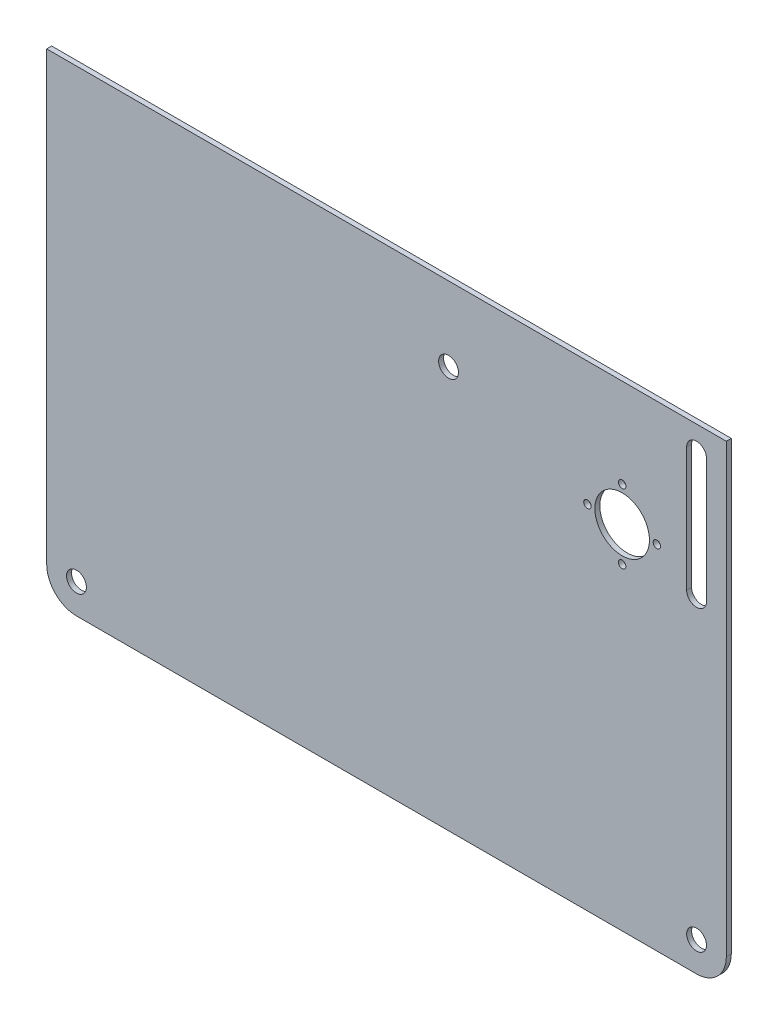
SolidWorks part; units mm, degrees
ref_plane "Front Plane" through (0, 0, 0) normal (0, 0, 1) x (1, 0, 0)
ref_plane "Top Plane" through (0, 0, 0) normal (0, 1, 0) x (1, 0, 0)
ref_plane "Right Plane" through (0, 0, 0) normal (1, 0, 0) x (0, 0, -1)
sketch "Sketch1" plane through (0, 0, 0) normal (0, 0, 1) x (1, 0, 0)
  line L0 (55, 0) -> (-55, 0) construction
  line L1 (0, 53.2731) -> (0, -38.9774) construction
  line L2 (0, -55) -> (0, 55) construction
  line L3 (-125, -12) -> (125, -12)
  line L4 (121, 120) -> (129, 120)
  line L5 (121, 120) -> (121, 170)
  line L6 (121, 170) -> (129, 170)
  line L7 (129, 120) -> (129, 170)
  line L8 (121, 120) -> (129, 170) construction
  line L9 (121, 170) -> (129, 120) construction
  line L10 (158.4448, 180) -> (-53.9982, 180)
  line L11 (137, 0) -> (137, 180)
  line L12 (137, 180) -> (158.4448, 180)
  line L13 (-53.9982, 180) -> (-137, 180)
  line L14 (-137, 180) -> (-137, 0)
  circle A0 centre (-125, 0) radius 4
  circle A1 centre (125, 0) radius 4
  circle A2 centre (125, 170) radius 4
  circle A3 centre (95, 130) radius 11
  circle A4 centre (25, 150) radius 4
  circle A5 centre (125, 120) radius 4
  arc A6 (-125, -12) -> (-137, 0) centre (-125, 0) cw
  arc A7 (125, -12) -> (137, 0) centre (125, 0) ccw
  circle A8 centre (95, 130) radius 14 construction
  circle A9 centre (95, 144) radius 1.5
  circle A10 centre (109, 130) radius 1.5
  circle A11 centre (95, 116) radius 1.5
  circle A12 centre (81, 130) radius 1.5
  point P17 (125, 145)
  point P44 (95, 130)
  dimension "D2" = 8
  dimension "D4" = 22
  dimension "D11" = 12
  dimension "D13" = 12
  dimension "D14" = 28
  dimension "D15" = 3
  dimension "D1" = 250
  dimension "D3" = 250
  dimension "D5" = 150
  dimension "D6" = 150
  dimension "D7" = 130
  dimension "D8" = 220
  dimension "D9" = 145
  dimension "D10" = 50
  dimension "D12" = 10
  dimension "D16" = 4
extrude "Boss-Extrude1" add sketch "Sketch1" along normal blind 2 contours L3 A7 L11 L12 L10 L13 L14 A6 A0 A1 A3 A4 A5 L5 A2 L7
